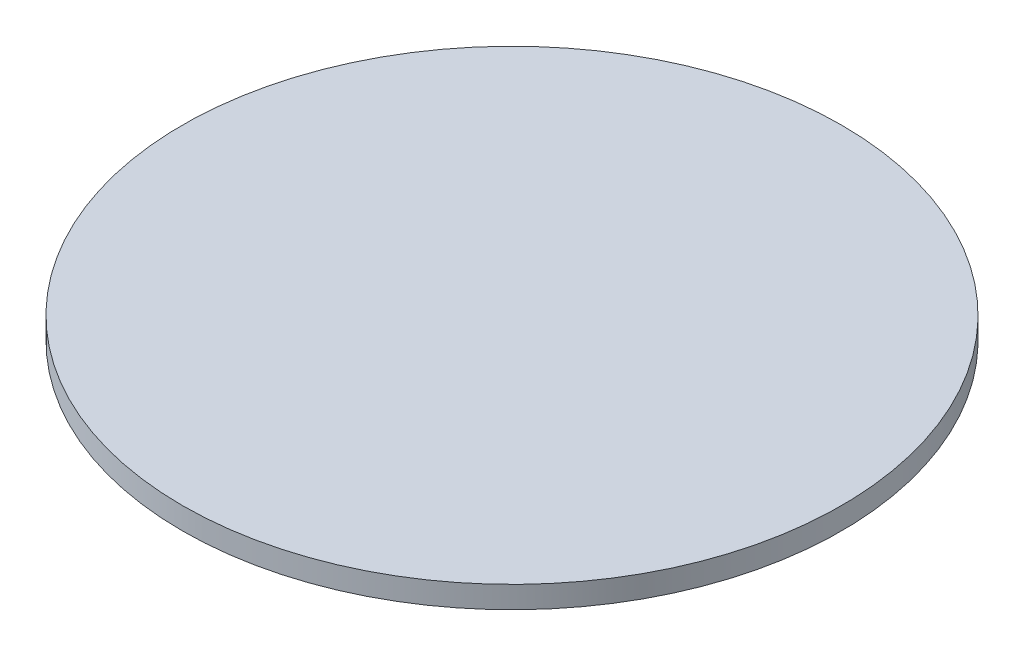
SolidWorks part; units mm, degrees
material "AISI 4340 Steel, normalized"
ref_plane "Front Plane" through (0, 0, 0) normal (0, 0, 1) x (1, 0, 0)
ref_plane "Top Plane" through (0, 0, 0) normal (0, 1, 0) x (1, 0, 0)
ref_plane "Right Plane" through (0, 0, 0) normal (1, 0, 0) x (0, 0, -1)
sketch "Sketch1" plane through (0, 0, 0) normal (0, 1, 0) x (1, 0, 0)
  circle A0 centre (0, 0) radius 38.1
  dimension "D1" = 76.2
extrude "Boss-Extrude1" add sketch "Sketch1" along normal blind 2.54
sketch "Sketch3" plane through (0, 0, 0) normal (0, 1, 0) x (1, 0, 0)
  line L0 (-37.6843, 22.9647) -> (37.6843, -22.9647) construction
  line L1 (-40.3146, -24.2798) -> (40.3146, 24.2798) construction
  point P6 (0, 0)
  point P7 (0, 0)
  dimension "D1" = 117.583
